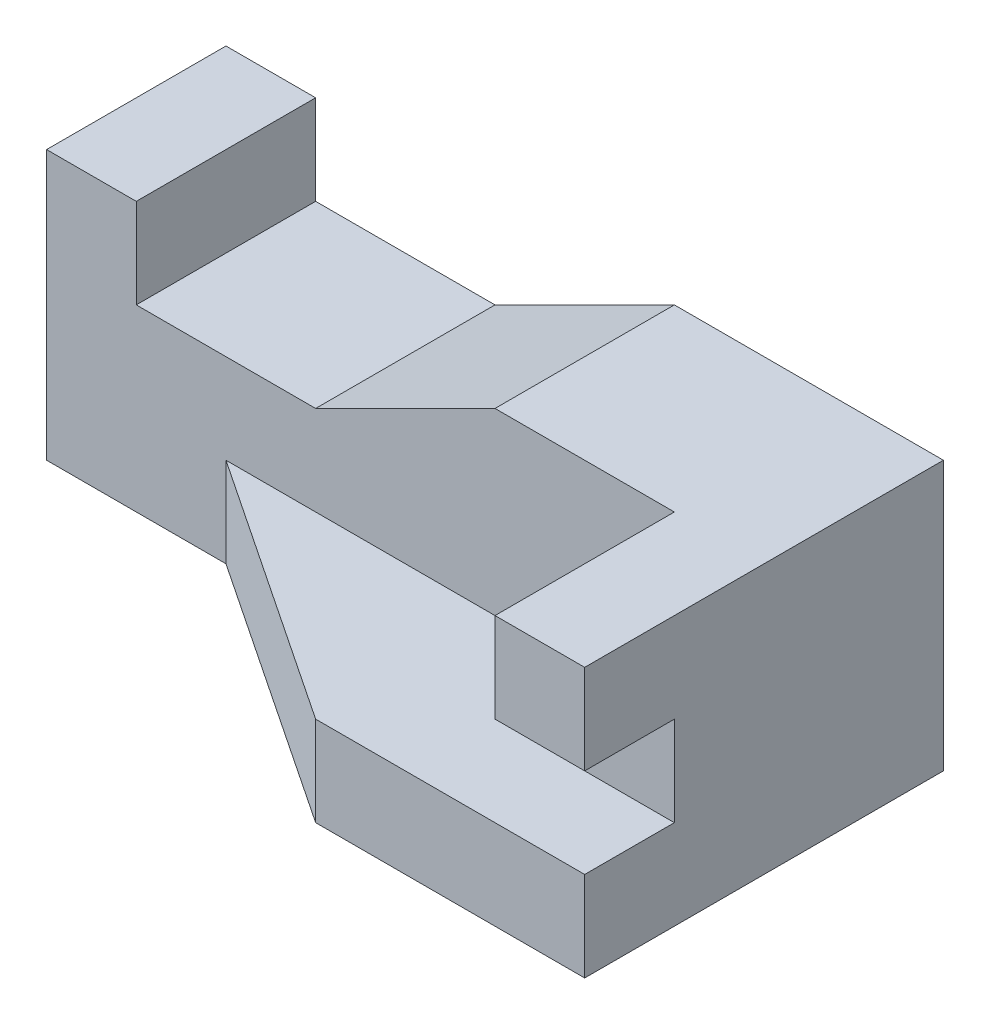
SolidWorks part; units mm, degrees
ref_plane "Front Plane" through (0, 0, 0) normal (0, 0, 1) x (1, 0, 0)
ref_plane "Top Plane" through (0, 0, 0) normal (0, 1, 0) x (1, 0, 0)
ref_plane "Right Plane" through (0, 0, 0) normal (1, 0, 0) x (0, 0, -1)
sketch "Sketch1" plane through (0, 0, 0) normal (0, 0, 1) x (1, 0, 0)
  line L0 (-29.0336, 12.7013) -> (-29.0336, 2.7013)
  line L1 (-39.0336, -17.2987) -> (40.9664, -17.2987)
  line L2 (-39.0336, -17.2987) -> (-39.0336, 12.7013)
  line L3 (-39.0336, 12.7013) -> (-29.0336, 12.7013)
  line L4 (40.9664, -17.2987) -> (40.9664, 12.7013)
  line L5 (-29.0336, 2.7013) -> (-9.0336, 2.7013)
  line L6 (-9.0336, 2.7013) -> (10.9664, 12.7013)
  line L7 (10.9664, 12.7013) -> (40.9664, 12.7013)
  point P0 (0, 0)
  dimension "D1" = 80
  dimension "D2" = 30
  dimension "D3" = 10
  dimension "D4" = 10
  dimension "D5" = 20
  dimension "D6" = 30
extrude "Boss-Extrude1" add sketch "Sketch1" along normal blind 20
sketch "Sketch2" plane through (0, 0, 20) normal (0, 0, 1) x (1, 0, 0)
  line L1 (40.9664, -17.2987) -> (10.9664, -17.2987)
  line L2 (40.9664, -17.2987) -> (40.9664, -7.2987)
  line L3 (40.9664, -7.2987) -> (10.9664, -7.2987)
  line L4 (10.9664, -17.2987) -> (10.9664, -7.2987)
  dimension "D1" = 30
  dimension "D2" = 10
extrude "Boss-Extrude2" add sketch "Sketch2" along normal blind 20
sketch "Sketch3" plane through (0, -17.2987, 0) normal (0, -1, 0) x (-1, 0, 0)
  line L0 (-10.9664, -40) -> (19.0336, -20)
  line L1 (39.0336, -20) -> (-10.9664, -20) construction
  line L2 (19.0336, -20) -> (-10.9664, -20)
  line L3 (-10.9664, -20) -> (-10.9664, -40)
  dimension "D1" = 20
extrude "Boss-Extrude3" add sketch "Sketch3" against normal blind 10
sketch "Sketch4" plane through (0, 0, 20) normal (0, 0, 1) x (1, 0, 0)
  line L0 (40.9664, -7.2987) -> (10.9664, -7.2987) construction
  line L1 (40.9664, 12.7013) -> (30.9664, 12.7013)
  line L2 (40.9664, 12.7013) -> (40.9664, -7.2987)
  line L3 (40.9664, -7.2987) -> (30.9664, -7.2987)
  line L4 (30.9664, 12.7013) -> (30.9664, -7.2987)
  dimension "D1" = 10
extrude "Boss-Extrude4" add sketch "Sketch4" along normal blind 10
sketch "Sketch5" plane through (0, 0, 30) normal (0, 0, 1) x (1, 0, 0)
  line L0 (40.9664, -7.2987) -> (40.9664, 12.7013) construction
  line L1 (30.9664, 12.7013) -> (40.9664, 12.7013)
  line L2 (30.9664, 12.7013) -> (30.9664, 2.7013)
  line L3 (30.9664, 2.7013) -> (40.9664, 2.7013)
  line L4 (40.9664, 12.7013) -> (40.9664, 2.7013)
  dimension "D1" = 10
extrude "Boss-Extrude5" add sketch "Sketch5" along normal blind 10
